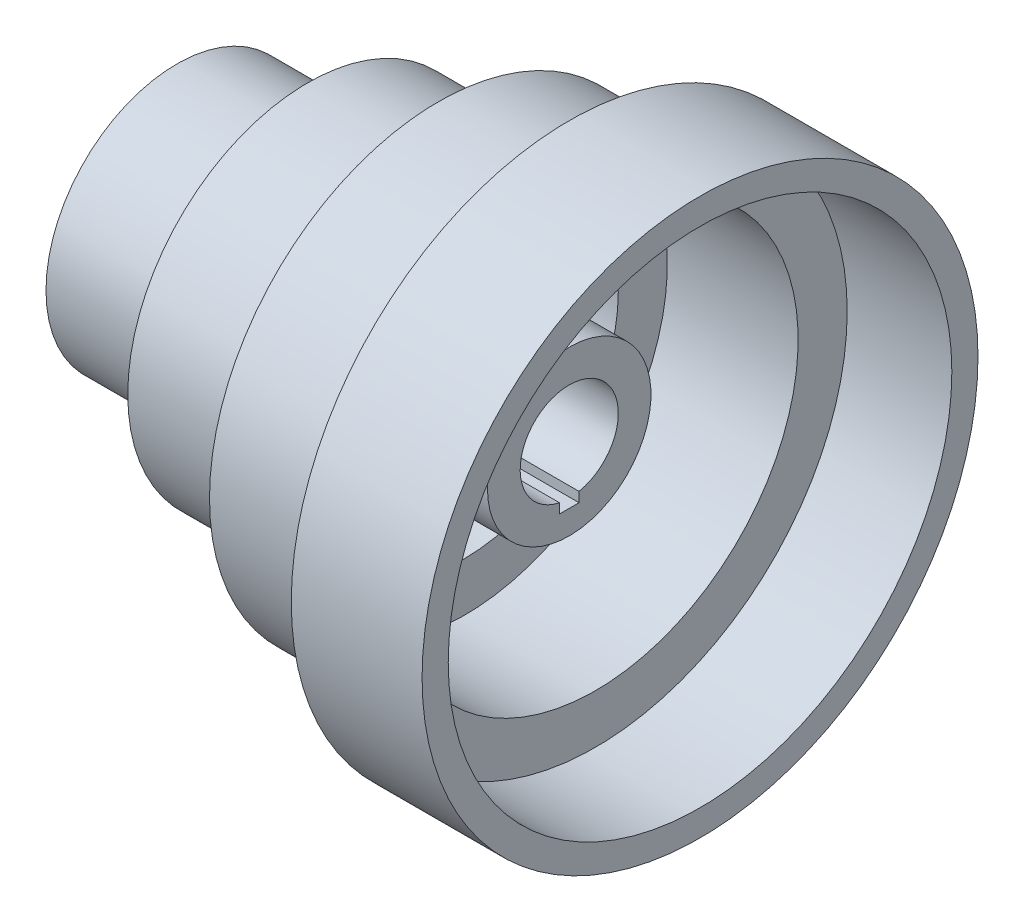
SolidWorks part; units mm, degrees
ref_plane "Front Plane" through (0, 0, 0) normal (0, 0, 1) x (1, 0, 0)
ref_plane "Top Plane" through (0, 0, 0) normal (0, 1, 0) x (1, 0, 0)
ref_plane "Right Plane" through (0, 0, 0) normal (1, 0, 0) x (0, 0, -1)
sketch "Sketch2" plane through (0, 0, 0) normal (0, 0, 1) x (1, 0, 0)
  line L0 (-111.6505, 0) -> (188.3495, 0) construction
  line L1 (0, 15) -> (120, 15)
  line L2 (120, 15) -> (120, 25)
  line L3 (120, 25) -> (48, 25)
  line L4 (48, 25) -> (48, 47)
  line L5 (48, 47) -> (88, 47)
  line L6 (88, 47) -> (88, 62)
  line L7 (88, 62) -> (128, 62)
  line L8 (128, 62) -> (128, 77)
  line L9 (128, 77) -> (160, 77)
  line L10 (160, 77) -> (160, 85)
  line L11 (160, 85) -> (120, 85)
  line L12 (120, 85) -> (120, 70)
  line L13 (120, 70) -> (80, 70)
  line L14 (80, 70) -> (80, 55)
  line L15 (80, 55) -> (40, 55)
  line L16 (40, 55) -> (40, 40)
  line L17 (40, 40) -> (0, 40)
  line L18 (0, 40) -> (0, 15)
  point P21 (0, 0)
  point P22 (0, 0)
  point P23 (0, 0)
  dimension "D1" = 40
  dimension "D2" = 10
  dimension "D3" = 40
  dimension "D4" = 40
  dimension "D5" = 120
  dimension "D6" = 8
  dimension "D7" = 8
  dimension "D8" = 8
  dimension "D9" = 15
  dimension "D10" = 160
  dimension "D11" = 40
  dimension "D12" = 55
  dimension "D13" = 70
  dimension "D14" = 85
  dimension "D15" = 8
  dimension "D16" = 8
  dimension "D17" = 8
  dimension "D18" = 300
  dimension "D19" = 54.1202
revolve "Revolve1" add sketch "Sketch2" angle 360 about L0
sketch "Sketch3" plane through (0, 0, 0) normal (-1, 0, 0) x (0, 0, 1)
  line L0 (0, 89.0887) -> (0, -96.9035) construction
  line L1 (-3, -14.6969) -> (-3, -17.6969)
  line L2 (-3, -17.6969) -> (3, -17.6969)
  line L3 (3, -17.6969) -> (3, -14.6969)
  arc A0 (3, -14.6969) -> (-3, -14.6969) centre (0, 0) ccw
  point P7 (0, 0)
  point P10 (0, 0)
  dimension "D4" = 30
  dimension "D1" = 6
  dimension "D3" = 3
extrude "Cut-Extrude1" cut sketch "Sketch3" against normal through all both and the other way through all
